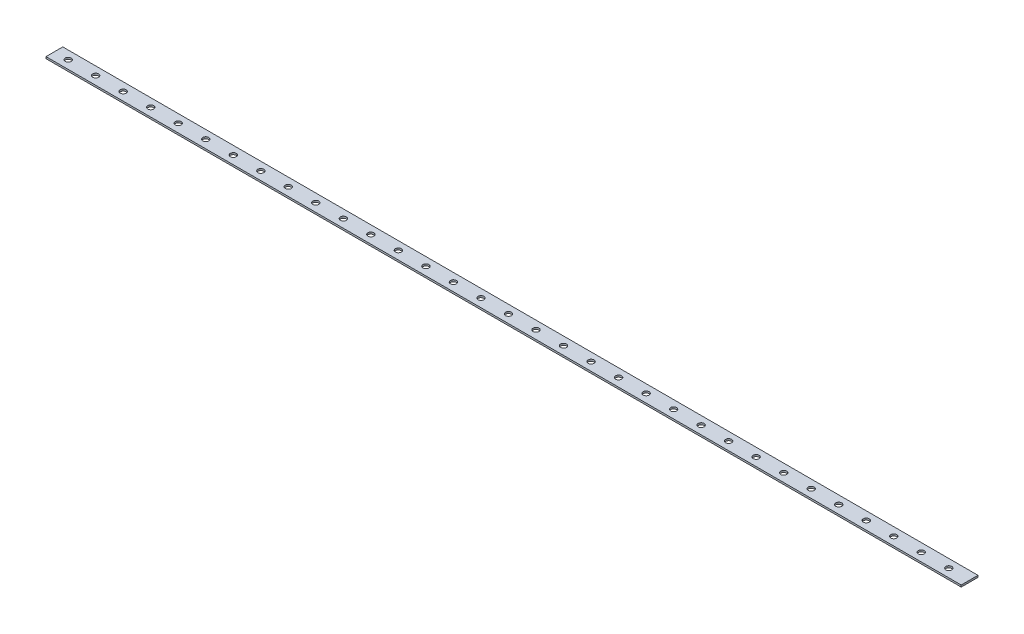
SolidWorks part; units mm, degrees
ref_plane "Front Plane" through (0, 0, 0) normal (0, 0, 1) x (1, 0, 0)
ref_plane "Top Plane" through (0, 0, 0) normal (0, 1, 0) x (1, 0, 0)
ref_plane "Right Plane" through (0, 0, 0) normal (1, 0, 0) x (0, 0, -1)
sketch "Sketch1" plane through (0, 0, 0) normal (0, 1, 0) x (1, 0, 0)
  line L0 (-459.5448, 0) -> (429.6654, 0) construction
  line L1 (-498.825, 9.15) -> (-498.825, -9.15)
  line L2 (-498.825, 9.15) -> (498.825, 9.15)
  line L3 (-498.825, -9.15) -> (498.825, -9.15)
  line L4 (0, 11.4722) -> (0, -16.6655) construction
  line L5 (498.825, 9.15) -> (498.825, -9.15)
  circle A0 centre (-483.825, 0) radius 3.25
  circle A1 centre (-453.825, 0) radius 3.25
  circle A2 centre (-423.825, 0) radius 3.25
  circle A3 centre (-393.825, 0) radius 3.25
  circle A4 centre (-363.825, 0) radius 3.25
  circle A5 centre (-333.825, 0) radius 3.25
  circle A6 centre (-303.825, 0) radius 3.25
  circle A7 centre (-273.825, 0) radius 3.25
  circle A8 centre (-243.825, 0) radius 3.25
  circle A9 centre (-213.825, 0) radius 3.25
  circle A10 centre (-183.825, 0) radius 3.25
  circle A11 centre (-153.825, 0) radius 3.25
  circle A12 centre (-123.825, 0) radius 3.25
  circle A13 centre (-93.825, 0) radius 3.25
  circle A14 centre (-63.825, 0) radius 3.25
  circle A15 centre (-33.825, 0) radius 3.25
  circle A16 centre (-3.825, 0) radius 3.25
  circle A17 centre (26.175, 0) radius 3.25
  circle A18 centre (56.175, 0) radius 3.25
  circle A19 centre (86.175, 0) radius 3.25
  circle A20 centre (116.175, 0) radius 3.25
  circle A21 centre (146.175, 0) radius 3.25
  circle A22 centre (176.175, 0) radius 3.25
  circle A23 centre (206.175, 0) radius 3.25
  circle A24 centre (236.175, 0) radius 3.25
  circle A25 centre (266.175, 0) radius 3.25
  circle A26 centre (296.175, 0) radius 3.25
  circle A27 centre (326.175, 0) radius 3.25
  circle A28 centre (356.175, 0) radius 3.25
  circle A29 centre (386.175, 0) radius 3.25
  circle A30 centre (416.175, 0) radius 3.25
  circle A31 centre (446.175, 0) radius 3.25
  circle A32 centre (476.175, 0) radius 3.25
  point P6 (-498.825, 0)
  point P11 (0, -9.15)
  point P12 (0, 9.15)
  dimension "D2" = 6.5
  dimension "D1" = 997.65
  dimension "D3" = 18.3
  dimension "D4" = 15
  dimension "D5" = 33
extrude "Boss-Extrude1" add sketch "Sketch1" along normal mid plane 2
